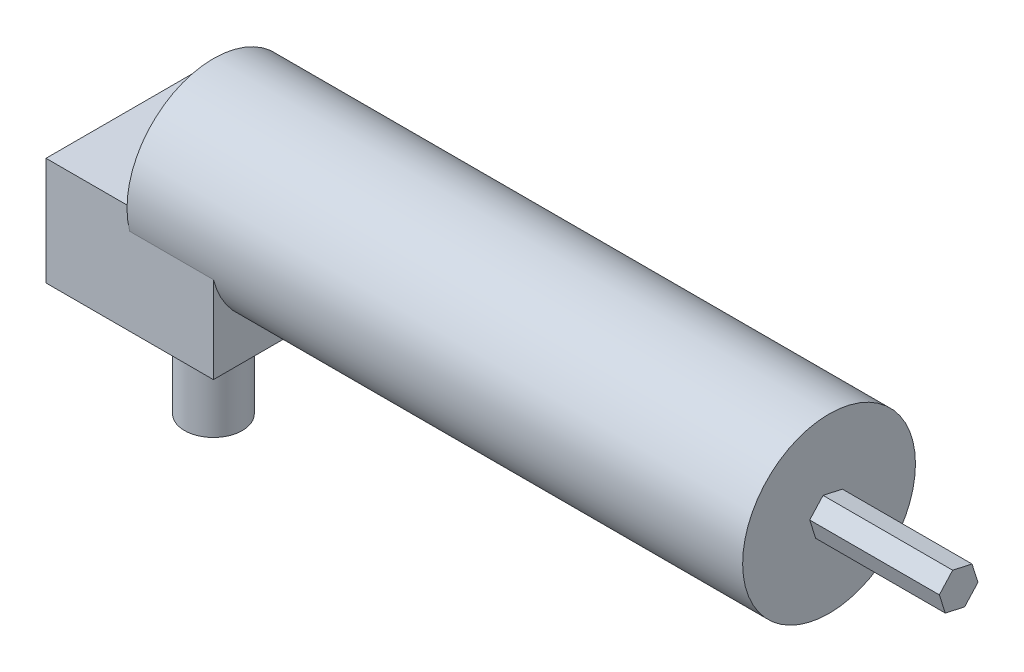
SolidWorks part; units mm, degrees
ref_plane "Front Plane" through (0, 0, 0) normal (0, 0, 1) x (1, 0, 0)
ref_plane "Top Plane" through (0, 0, 0) normal (0, 1, 0) x (1, 0, 0)
ref_plane "Right Plane" through (0, 0, 0) normal (1, 0, 0) x (0, 0, -1)
sketch "Sketch1" plane through (0, 0, 0) normal (0, 1, 0) x (1, 0, 0)
  line L1 (-15.5, -15.5) -> (15.5, -15.5)
  line L2 (-15.5, -15.5) -> (-15.5, 15.5)
  line L3 (-15.5, 15.5) -> (15.5, 15.5)
  line L4 (15.5, -15.5) -> (15.5, 15.5)
  line L5 (-15.5, -15.5) -> (15.5, 15.5) construction
  line L6 (-15.5, 15.5) -> (15.5, -15.5) construction
  point P0 (0, 0)
  dimension "D1" = 31
extrude "Boss-Extrude1" add sketch "Sketch1" along normal blind 20
sketch "Sketch2" plane through (0, 0, 0) normal (1, 0, 0) x (0, 0, -1)
  line L0 (-15.5, 20) -> (15.5, 20) construction
  circle A0 centre (0, 20) radius 16
  dimension "D1" = 32
extrude "Boss-Extrude2" add sketch "Sketch2" along normal blind 114
sketch "Sketch3" plane through (114, 0, 0) normal (1, 0, 0) x (0, 0, -1)
  line L1 (2.4698, 22.7094) -> (-1.1115, 23.4936)
  line L2 (-1.1115, 23.4936) -> (-3.5813, 20.7842)
  line L3 (-3.5813, 20.7842) -> (-2.4698, 17.2906)
  line L4 (-2.4698, 17.2906) -> (1.1115, 16.5064)
  line L5 (1.1115, 16.5064) -> (3.5813, 19.2158)
  line L6 (3.5813, 19.2158) -> (2.4698, 22.7094)
  circle A0 centre (0, 20) radius 3.175 construction
  dimension "D1" = 6.35
extrude "Boss-Extrude3" add sketch "Sketch3" along normal blind 24
sketch "Sketch4" plane through (0, 0, 0) normal (0, -1, 0) x (1, 0, 0)
  circle A0 centre (0, 0) radius 5.35
  dimension "D1" = 10.7
extrude "Boss-Extrude4" add sketch "Sketch4" along normal blind 21
sketch "Sketch5" plane through (0, -21, 0) normal (0, -1, 0) x (1, 0, 0)
  line L1 (-3.9485, -0.8619) -> (-1.2278, -3.8504)
  line L2 (-1.2278, -3.8504) -> (2.7207, -2.9885)
  line L3 (2.7207, -2.9885) -> (3.9485, 0.8619)
  line L4 (3.9485, 0.8619) -> (1.2278, 3.8504)
  line L5 (1.2278, 3.8504) -> (-2.7207, 2.9885)
  line L6 (-2.7207, 2.9885) -> (-3.9485, -0.8619)
  circle A0 centre (0, 0) radius 3.5 construction
  dimension "D1" = 7
extrude "Cut-Extrude1" cut sketch "Sketch5" against normal blind 7.41
